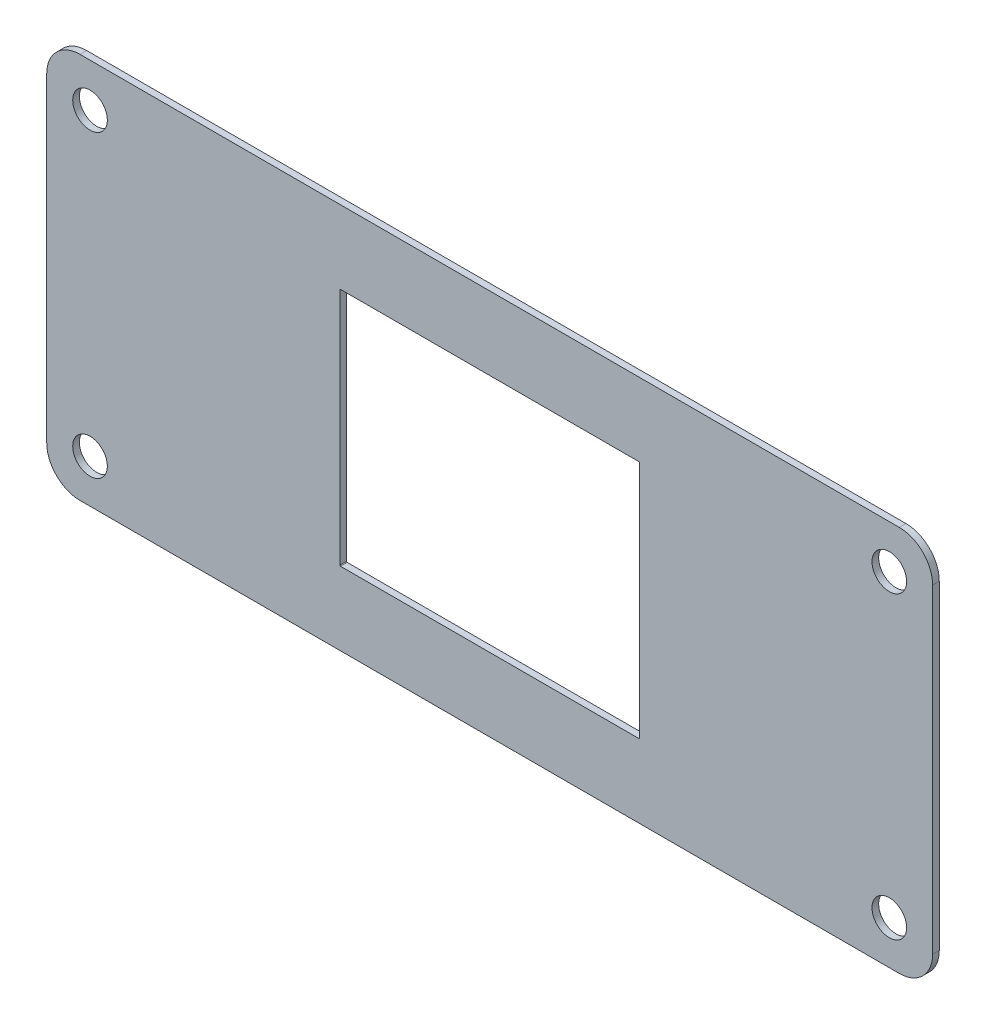
SolidWorks part; units mm, degrees
ref_plane "Front Plane" through (0, 0, 0) normal (0, 0, 1) x (1, 0, 0)
ref_plane "Top Plane" through (0, 0, 0) normal (0, 1, 0) x (1, 0, 0)
ref_plane "Right Plane" through (0, 0, 0) normal (1, 0, 0) x (0, 0, -1)
sketch "Sketch1" plane through (0, 0, 0) normal (0, 0, 1) x (1, 0, 0)
  line L1 (-66.5, -29) -> (66.5, -29)
  line L2 (-66.5, -29) -> (-66.5, 29)
  line L3 (-66.5, 29) -> (66.5, 29)
  line L4 (66.5, -29) -> (66.5, 29)
  line L5 (-66.5, -29) -> (66.5, 29) construction
  line L6 (-66.5, 29) -> (66.5, -29) construction
  point P0 (0, 0)
  dimension "D1" = 133
  dimension "D2" = 58
extrude "Boss-Extrude1" add sketch "Sketch1" along normal blind 1
sketch "Sketch2" plane through (0, 0, 0) normal (0, 0, 1) x (1, 0, 0)
  line L1 (-22.4, -18) -> (22.4, -18)
  line L2 (-22.5, -17.9) -> (-22.5, 17.9)
  line L3 (-22.4, 18) -> (22.4, 18)
  line L4 (22.5, -17.9) -> (22.5, 17.9)
  line L5 (-22.5, -18) -> (22.5, 18) construction
  line L6 (-22.5, 18) -> (22.5, -18) construction
  arc A0 (22.5, -17.9) -> (22.4, -18) centre (22.4, -17.9) cw
  arc A1 (-22.4, -18) -> (-22.5, -17.9) centre (-22.4, -17.9) cw
  arc A2 (22.5, 17.9) -> (22.4, 18) centre (22.4, 17.9) ccw
  arc A3 (-22.4, 18) -> (-22.5, 17.9) centre (-22.4, 17.9) ccw
  point P0 (0, 0)
  dimension "D3" = 0.1
  dimension "D1" = 36
  dimension "D2" = 45
extrude "Cut-Extrude1" cut sketch "Sketch2" along normal up to next
fillet "Fillet1" radius 5 4 edges at (-66.5, -29, 0.5) (66.5, -29, 0.5) (66.5, 29, 0.5) (-66.5, 29, 0.5)
sketch "Sketch3" plane through (0, 0, 0) normal (0, 0, 1) x (1, 0, 0)
  line L2 (0, -0.55) -> (0, 0.55) construction
  line L3 (0.55, 0) -> (-0.55, 0) construction
  circle A0 centre (-60, 22.5) radius 2.6
  circle A1 centre (60, 22.5) radius 2.6
  circle A2 centre (60, -22.5) radius 2.6
  circle A3 centre (-60, -22.5) radius 2.6
  dimension "D1" = 5.2
  dimension "D2" = 60
  dimension "D3" = 22.5
extrude "Cut-Extrude2" cut sketch "Sketch3" along normal up to next
